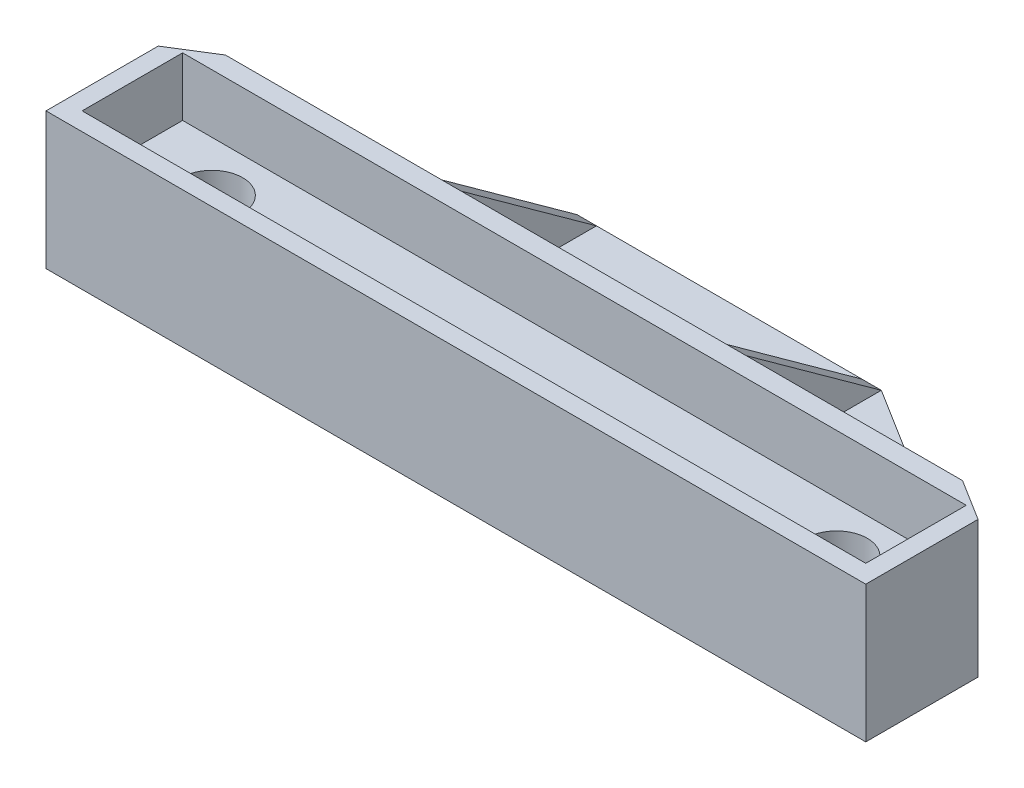
SolidWorks part; units mm, degrees
ref_plane "Front Plane" through (0, 0, 0) normal (0, 0, 1) x (1, 0, 0)
ref_plane "Top Plane" through (0, 0, 0) normal (0, 1, 0) x (1, 0, 0)
ref_plane "Right Plane" through (0, 0, 0) normal (1, 0, 0) x (0, 0, -1)
sketch "Sketch1" plane through (0, 0, 0) normal (0, 1, 0) x (1, 0, 0)
  line L0 (0, 0) -> (0, 13.8356) construction
  line L1 (-18.9996, 7) -> (18.9996, 7)
  line L2 (-21, 5.75) -> (-21, 0)
  line L3 (-21, 0) -> (21, 0)
  line L4 (21, 5.75) -> (21, 0)
  line L5 (21, 5.75) -> (18.9996, 7)
  line L6 (-21, 5.75) -> (-18.9996, 7)
  point P0 (0, 0)
  dimension "D1" = 32
  dimension "D2" = 42
  dimension "D3" = 7
  dimension "D4" = 5.75
extrude "Riser" add sketch "Sketch1" along normal blind 7
sketch "Sketch2" plane through (0, 0, 0) normal (0, -1, 0) x (1, 0, 0)
  line L1 (0, 0) -> (0, -7) construction
  line L2 (-21, 0) -> (21, 0) construction
  line L4 (18.9996, -7) -> (-18.9996, -7) construction
  line L5 (21, 0) -> (21, -5.75) construction
  circle A0 centre (16, -3.5) radius 1.575
  circle A2 centre (-16, -3.5) radius 1.575
  point P12 (0, -3.5)
  dimension "D2" = 3.15
  dimension "D1" = 5
extrude "Mounting Holes" cut sketch "Sketch2" against normal through all
sketch "Sketch3" plane through (0, 7, 0) normal (0, 1, 0) x (1, 0, 0)
  line L5 (18.9996, 7) -> (-18.9996, 7) construction
  line L12 (-20.075, 6.075) -> (20.075, 6.075)
  line L13 (-20.075, 6.075) -> (-20.075, 0.925)
  line L14 (-20.075, 0.925) -> (20.075, 0.925)
  line L15 (20.075, 6.075) -> (20.075, 0.925)
  line L16 (21, 0) -> (21, 5.75) construction
  dimension "D1" = 5.15
  dimension "D2" = 40.15
  dimension "D3" = 0.925
  dimension "D4" = 0.925
extrude "Recess" cut sketch "Sketch3" against normal blind 3 contours L12 L15 L14 L13
sketch "Sketch4" plane through (0, 0, 0) normal (0, 1, 0) x (1, 0, 0)
  line L0 (-28.0926, 1.318) -> (7.8348, 23.768) construction
  line L1 (-18.9996, 7) -> (18.9996, 7)
  line L3 (7.7972, 14) -> (-7.7972, 14)
  line L4 (-7.7972, 14) -> (-18.9996, 7)
  line L5 (0, 0) -> (0, 16.9853) construction
  line L6 (7.7972, 14) -> (18.9996, 7)
  dimension "D1" = 32
  dimension "D2" = 7
extrude "Flange" add sketch "Sketch4" along normal blind 7
sketch "Sketch5" plane through (0, 7, 0) normal (0, 1, 0) x (1, 0, 0)
  line L0 (-6.7972, 7.075) -> (-6.7972, 14)
  line L1 (7.7972, 14) -> (-7.7972, 14) construction
  line L2 (-6.7972, 14) -> (6.7972, 14)
  line L3 (6.7972, 14) -> (6.7972, 7.075)
  line L4 (6.7972, 7.075) -> (-6.7972, 7.075)
  line L5 (-18.8796, 7.075) -> (-7.7972, 7.075)
  line L8 (-7.7972, 14) -> (-21, 5.75) construction
  line L9 (-7.7972, 7.075) -> (-7.7972, 14)
  line L10 (-7.7972, 14) -> (-18.8796, 7.075)
  line L11 (0, 0) -> (0, 24.5183) construction
  line L12 (7.7972, 7.075) -> (7.7972, 14)
  line L13 (18.8796, 7.075) -> (7.7972, 7.075)
  line L14 (7.7972, 14) -> (18.8796, 7.075)
  line L15 (-20.075, 6.075) -> (20.075, 6.075) construction
  dimension "D1" = 1
  dimension "D2" = 1
  dimension "D4" = 1
extrude "Flange Cutout" cut sketch "Sketch5" against normal blind 5
sketch "Sketch7" plane through (6.7972, 0, 0) normal (-1, 0, 0) x (0, 0, 1)
  line L0 (-7.075, 7) -> (-14, 2)
  line L1 (-14, 2) -> (-14, 7)
  line L2 (-14, 7) -> (-7.075, 7)
extrude "Angle Cutout" cut sketch "Sketch7" against normal through all and the other way through all
chamfer "Flange Chamfer" distance 1 angle 45 3 edges at (0, 2, -7.075) (13.3384, 2, -7.075) (-13.3384, 2, -7.075)
